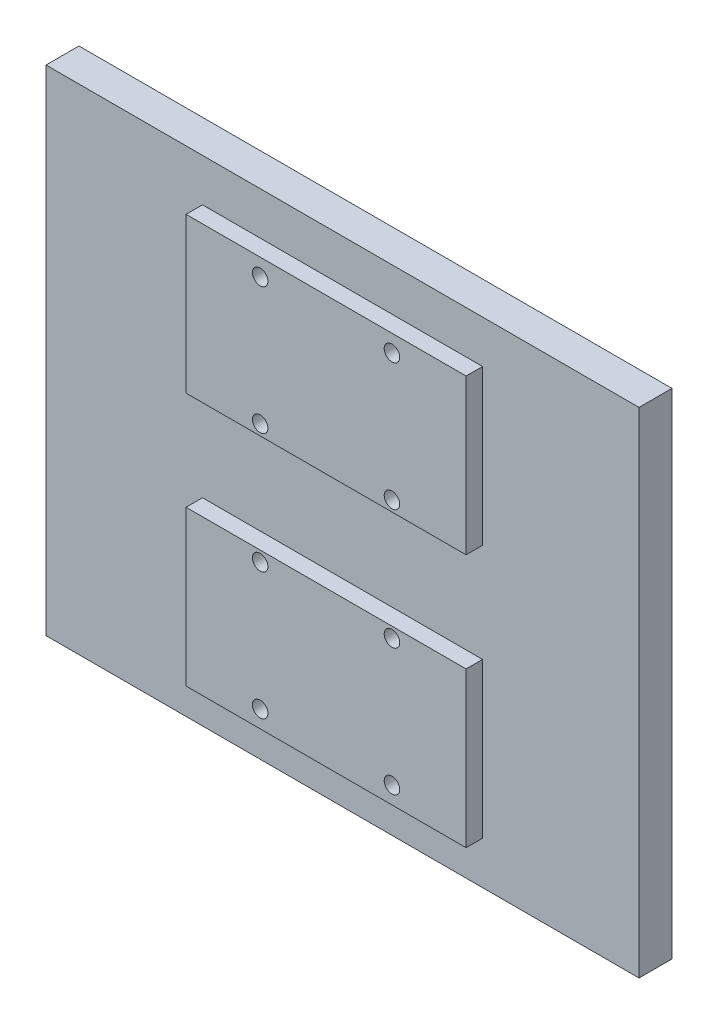
SolidWorks part; units mm, degrees
ref_plane "Ebene vorne" through (0, 0, 0) normal (0, 0, 1) x (1, 0, 0)
ref_plane "Ebene oben" through (0, 0, 0) normal (0, 1, 0) x (1, 0, 0)
ref_plane "Ebene rechts" through (0, 0, 0) normal (1, 0, 0) x (0, 0, -1)
sketch "Skizze1" plane through (0, 0, 0) normal (0, 0, 1) x (1, 0, 0)
  line L1 (-90, 75) -> (90, 75)
  line L2 (-90, 75) -> (-90, -75)
  line L3 (-90, -75) -> (90, -75)
  line L4 (90, 75) -> (90, -75)
  line L5 (-90, 75) -> (90, -75) construction
  line L6 (-90, -75) -> (90, 75) construction
  point P0 (0, 0)
  dimension "D1" = 150
  dimension "D2" = 180
extrude "Aufsatz-Linear austragen1" add sketch "Skizze1" along normal blind 10
sketch "Skizze2" plane through (0, 0, 10) normal (0, 0, 1) x (1, 0, 0)
  line L1 (-42.5, 62) -> (42.5, 62)
  line L2 (-42.5, 62) -> (-42.5, 15)
  line L3 (-42.5, 15) -> (42.5, 15)
  line L4 (42.5, 62) -> (42.5, 15)
  line L5 (-42.5, 62) -> (42.5, 15) construction
  line L6 (-42.5, 15) -> (42.5, 62) construction
  point P0 (0, 38.5)
  dimension "D1" = 47
  dimension "D2" = 85
  dimension "D3" = 0
  dimension "D4" = 15
extrude "Aufsatz-Linear austragen2" add sketch "Skizze2" along normal blind 5
sketch "Skizze3" plane through (0, 0, 15) normal (0, 0, 1) x (1, 0, 0)
  line L1 (-20, 18.2) -> (20, 18.2)
  line L2 (-20, 18.2) -> (-20, 56.8)
  line L3 (-20, 56.8) -> (20, 56.8)
  line L4 (20, 18.2) -> (20, 56.8)
  line L5 (-20, 18.2) -> (20, 56.8) construction
  line L6 (-20, 56.8) -> (20, 18.2) construction
  line L7 (-42.5, 62) -> (-42.5, 15) construction
  line L8 (42.5, 62) -> (-42.5, 62) construction
  point P0 (0, 37.5)
  dimension "D1" = 40
  dimension "D2" = 38.6
  dimension "D3" = 42.5
  dimension "D4" = 24.5
  dimension "D5" = 5.2
sketch "Skizze4" plane through (0, 0, 15) normal (0, 0, 1) x (1, 0, 0)
  circle A0 centre (-20, 56.8) radius 2.35
  circle A1 centre (-20, 18.2) radius 2.35
  circle A2 centre (20, 56.8) radius 2.35
  circle A3 centre (20, 18.2) radius 2.35
  dimension "D1" = 4.7
  dimension "D2" = 4.7
  dimension "D3" = 4.7
  dimension "D4" = 4.7
extrude "Schnitt-Linear austragen1" cut sketch "Skizze4" against normal through all both and the other way through all
sketch "Skizze5" plane through (0, 0, 0) normal (0, 0, -1) x (-1, 0, 0)
  circle A0 centre (-20, 56.8) radius 4.5
  circle A1 centre (20, 56.8) radius 4.5
  circle A2 centre (20, 18.2) radius 4.5
  circle A3 centre (-20, 18.2) radius 4.5
  dimension "D1" = 9
  dimension "D2" = 9
  dimension "D3" = 9
  dimension "D4" = 9
extrude "Schnitt-Linear austragen2" cut sketch "Skizze5" against normal blind 9
ref_plane "Ebene1" through (0, 0, 0) normal (0, 1, 0) x (1, 0, 0)
mirror "Spiegeln8" about plane through (0, 0, 0) normal (0, 1, 0) of "Aufsatz-Linear austragen2", "Schnitt-Linear austragen1", "Schnitt-Linear austragen2"
